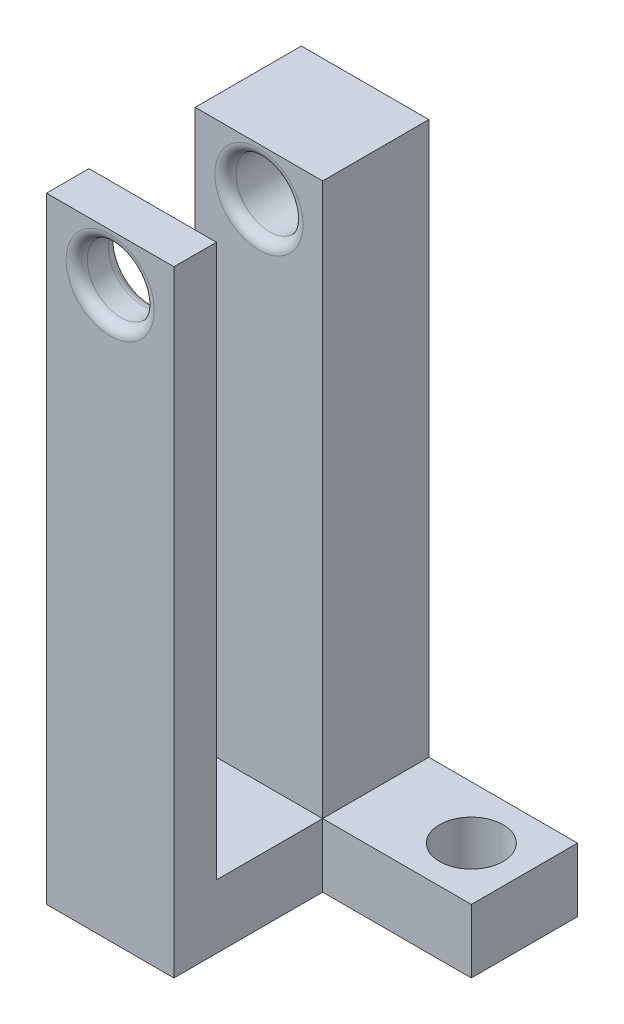
SolidWorks part; units mm, degrees
ref_plane "Front Plane" through (0, 0, 0) normal (0, 0, 1) x (1, 0, 0)
ref_plane "Top Plane" through (0, 0, 0) normal (0, 1, 0) x (1, 0, 0)
ref_plane "Right Plane" through (0, 0, 0) normal (1, 0, 0) x (0, 0, -1)
sketch "Sketch1" plane through (0, 0, 0) normal (0, 1, 0) x (1, 0, 0)
  line L0 (-10, 4.0757) -> (10, 4.0757)
  line L1 (10, 4.0757) -> (10, -0.9243)
  line L2 (10, -0.9243) -> (3, -0.9243)
  line L3 (3, -0.9243) -> (3, -7.9243)
  line L4 (3, -7.9243) -> (-3, -7.9243)
  line L5 (-3, -7.9243) -> (-3, -0.9243)
  line L6 (-3, -0.9243) -> (-10, -0.9243)
  line L7 (-10, -0.9243) -> (-10, 4.0757)
  line L8 (7.5, 1.5757) -> (-7.5, 1.5757) construction
  circle A0 centre (7.5, 1.5757) radius 1.5
  circle A1 centre (-7.5, 1.5757) radius 1.5
  point P2 (0, 4.0757)
  point P11 (-10, 1.5757)
  point P12 (0, 1.5757)
  point P13 (0, 0)
  point P18 (10, 1.5757)
  dimension "D6" = 3
  dimension "D1" = 20
  dimension "D2" = 5
  dimension "D3" = 6
  dimension "D4" = 7
  dimension "D5" = 15
extrude "Boss-Extrude1" add sketch "Sketch1" along normal blind 3
sketch "Sketch2" plane through (0, 3, 0) normal (0, 1, 0) x (1, 0, 0)
  line L0 (10, 4.0757) -> (-10, 4.0757) construction
  line L1 (-3, -0.9243) -> (3, -0.9243)
  line L2 (-3, -0.9243) -> (-3, 4.0757)
  line L3 (-3, 4.0757) -> (3, 4.0757)
  line L4 (3, -0.9243) -> (3, 4.0757)
  line L5 (3, -7.9243) -> (3, -0.9243) construction
  line L6 (-3, -7.9243) -> (3, -7.9243)
  line L7 (-3, -7.9243) -> (-3, -5.9243)
  line L8 (-3, -5.9243) -> (3, -5.9243)
  line L9 (3, -7.9243) -> (3, -5.9243)
  dimension "D1" = 2
extrude "Boss-Extrude2" add sketch "Sketch2" along normal blind 26
sketch "Sketch3" plane through (0, 0, -4.0757) normal (0, 0, -1) x (-1, 0, 0)
  line L0 (3, 3) -> (10, 3) construction
  circle A0 centre (0, 26.75) radius 1.575
  dimension "D2" = 3.15
  dimension "D1" = 23.75
extrude "Cut-Extrude1" cut sketch "Sketch3" against normal up to surface (12 mm away) up to face at (0, 14.5, 7.9243)
fillet "Fillet1" radius 0.5 4 edges at (1.575, 26.75, 5.9243) (-1.575, 26.75, 7.9243) (-1.575, 26.75, 0.9243) (-1.575, 26.75, -4.0757)
